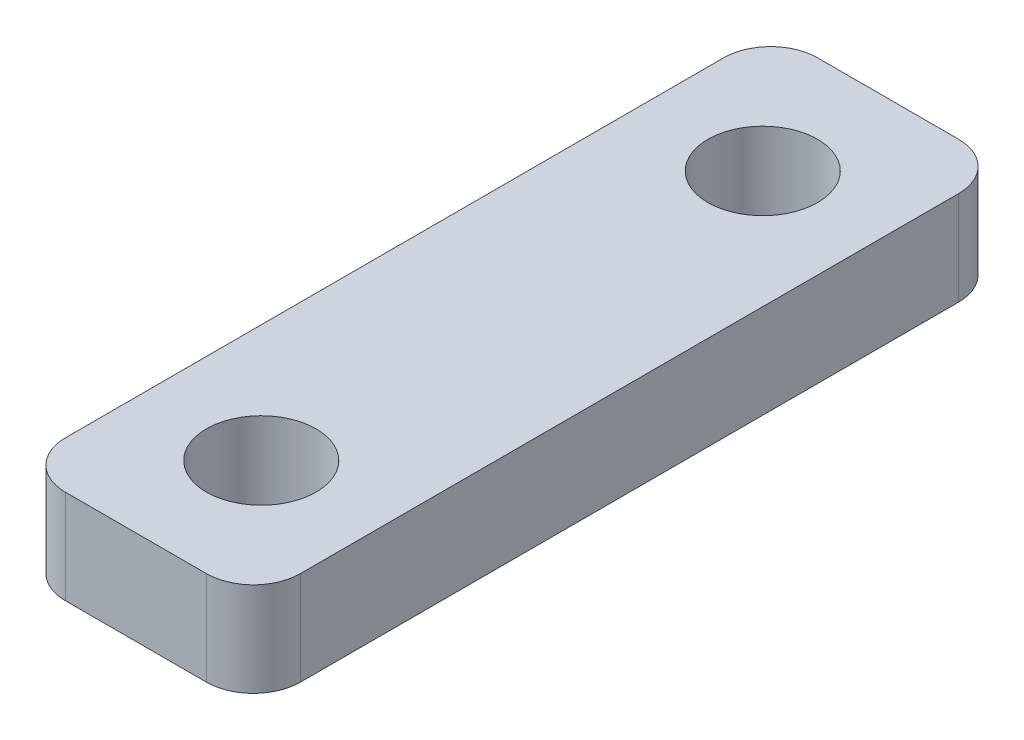
SolidWorks part; units mm, degrees
ref_plane "Front Plane" through (0, 0, 0) normal (0, 0, 1) x (1, 0, 0)
ref_plane "Top Plane" through (0, 0, 0) normal (0, 1, 0) x (1, 0, 0)
ref_plane "Right Plane" through (0, 0, 0) normal (1, 0, 0) x (0, 0, -1)
sketch "Sketch1" plane through (0, 0, 0) normal (0, 1, 0) x (1, 0, 0)
  line L0 (0, 0) -> (0, 42)
  line L1 (3, 45) -> (12, 45)
  line L2 (15, 42) -> (15, 0)
  line L3 (12, -3) -> (3, -3)
  arc A0 (0, 42) -> (3, 45) centre (3, 42) cw
  arc A1 (12, 45) -> (15, 42) centre (12, 42) cw
  arc A2 (15, 0) -> (12, -3) centre (12, 0) cw
  arc A3 (3, -3) -> (0, 0) centre (3, 0) cw
  circle A4 centre (7.5, 37) radius 3.5
  circle A5 centre (7.5, 5) radius 3.5
  dimension "D2" = 3
  dimension "D3" = 3
  dimension "D4" = 3
  dimension "D5" = 3
  dimension "D9" = 7
  dimension "D10" = 7
  dimension "D6" = 15
  dimension "D7" = 32
  dimension "D8" = 7.5
  dimension "D11" = 7.5
  dimension "D12" = 8
  dimension "D13" = 8
extrude "Boss-Extrude1" add sketch "Sketch1" along normal blind 6
